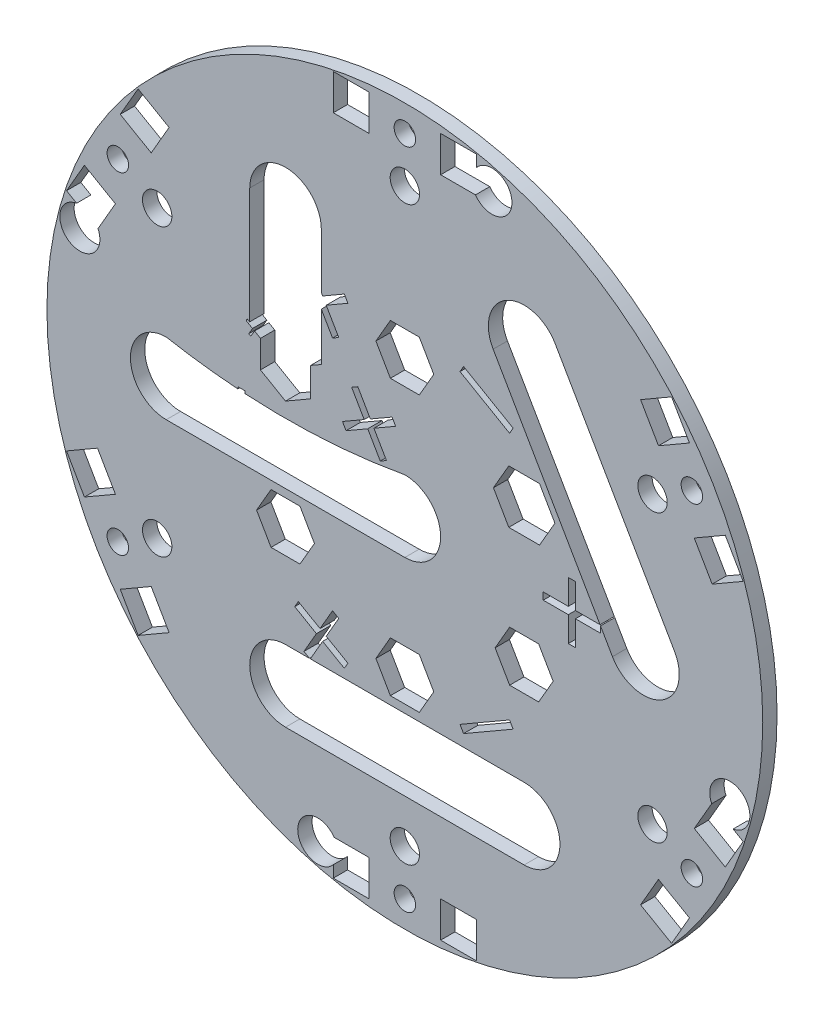
SolidWorks part; units mm, degrees
ref_plane "Plan de face" through (0, 0, 0) normal (0, 0, 1) x (1, 0, 0)
ref_plane "Plan de dessus" through (0, 0, 0) normal (0, 1, 0) x (1, 0, 0)
ref_plane "Plan de droite" through (0, 0, 0) normal (1, 0, 0) x (0, 0, -1)
sketch "Esquisse1" plane through (0, 0, 0) normal (0, 0, 1) x (1, 0, 0)
  line L0 (53.6751, 0) -> (-86.559, 0) construction
  line L1 (0, 50) -> (0, -56.2363) construction
  line L2 (0, 0) -> (70.5826, 40.7509) construction
  line L3 (0, 0) -> (-77.9761, 45.0195) construction
  line L4 (16.6667, 28.8675) -> (33.3333, 0) construction
  line L5 (20.9968, 31.3675) -> (37.6635, 2.5)
  line L6 (12.3365, 26.3675) -> (29.0032, -2.5)
  line L7 (16.6667, -28.8675) -> (-16.6667, -28.8675) construction
  line L8 (16.6667, -33.8675) -> (-16.6667, -33.8675)
  line L9 (16.6667, -23.8675) -> (-16.6667, -23.8675)
  line L10 (-33.3333, 0) -> (0, 0) construction
  line L11 (-21.6707, 12.5116) -> (-20.1709, 11.6468)
  line L12 (-33.3333, -5) -> (0, -5)
  line L13 (-16.6714, 9.6252) -> (-16.6667, 28.8675) construction
  line L14 (-21.6707, 12.5116) -> (-21.6667, 28.8687)
  line L15 (-11.6707, 12.5116) -> (-11.6667, 28.8663)
  line L16 (-13.1709, 11.6451) -> (-11.6707, 12.5116)
  line L17 (-12.6299, -9.6252) -> (-14.6507, -6.1252)
  line L18 (-14.6507, -6.1252) -> (-18.6921, -6.1252)
  line L19 (-18.6921, -6.1252) -> (-20.7128, -9.6252)
  line L20 (-20.7128, -9.6252) -> (-18.6921, -13.1252)
  line L21 (-18.6921, -13.1252) -> (-14.6507, -13.1252)
  line L22 (-14.6507, -13.1252) -> (-12.6299, -9.6252)
  line L23 (2.0207, -15.7328) -> (-2.0207, -15.7328)
  line L24 (-2.0207, -15.7328) -> (-4.0415, -19.2328)
  line L25 (-4.0415, -19.2328) -> (-2.0207, -22.7328)
  line L26 (-2.0207, -22.7328) -> (2.0207, -22.7328)
  line L27 (2.0207, -22.7328) -> (4.0415, -19.2328)
  line L28 (4.0415, -19.2328) -> (2.0207, -15.7328)
  line L29 (14.64, -6.1122) -> (12.6134, -9.6225)
  line L30 (12.6134, -9.6225) -> (14.64, -13.1328)
  line L31 (14.64, -13.1328) -> (18.6933, -13.1328)
  line L32 (18.6933, -13.1328) -> (20.72, -9.6225)
  line L33 (20.72, -9.6225) -> (18.6933, -6.1122)
  line L34 (18.6933, -6.1122) -> (14.64, -6.1122)
  line L35 (20.9633, 9.6242) -> (18.8164, 13.3427)
  line L36 (18.8164, 13.3427) -> (14.5227, 13.3427)
  line L37 (14.5227, 13.3427) -> (12.3758, 9.6242)
  line L38 (12.3758, 9.6242) -> (14.5227, 5.9057)
  line L39 (14.5227, 5.9057) -> (18.8164, 5.9057)
  line L40 (18.8164, 5.9057) -> (20.9633, 9.6242)
  line L41 (4.0415, 19.1653) -> (2.0207, 22.6653)
  line L42 (2.0207, 22.6653) -> (-2.0207, 22.6653)
  line L43 (-2.0207, 22.6653) -> (-4.0415, 19.1653)
  line L44 (-4.0415, 19.1653) -> (-2.0207, 15.6653)
  line L45 (-2.0207, 15.6653) -> (2.0207, 15.6653)
  line L46 (2.0207, 15.6653) -> (4.0415, 19.1653)
  line L47 (-20.1709, 11.6468) -> (-20.1719, 7.6054)
  line L48 (-20.1719, 7.6054) -> (-16.6724, 5.5838)
  line L49 (-16.6724, 5.5838) -> (-13.1719, 7.6036)
  line L50 (-13.1719, 7.6036) -> (-13.1709, 11.6451)
  line L52 (-16.6704, 13.6667) -> (-20.1709, 11.6468) [skipped]
  line L53 (-13.1709, 11.6451) -> (-16.6704, 13.6667) [skipped]
  circle A0 centre (0, 0) radius 50
  circle A1 centre (33.3333, 0) radius 16.6667 construction
  circle A2 centre (16.6667, -28.8675) radius 16.6667 construction
  circle A3 centre (-16.6667, -28.8675) radius 16.6667 construction
  circle A4 centre (-33.3333, 0) radius 16.6667 construction
  circle A5 centre (-16.6667, 28.8675) radius 16.6667 construction
  circle A6 centre (16.6667, 28.8675) radius 16.6667 construction
  circle A7 centre (-34.5978, 19.9751) radius 2.05
  circle A8 centre (0, 39.9502) radius 2.05
  circle A9 centre (34.5978, 19.9751) radius 2.05
  circle A10 centre (34.5978, -19.9751) radius 2.05
  circle A11 centre (0, -39.9502) radius 2.05
  circle A12 centre (-34.5978, -19.9751) radius 2.05
  arc A13 (20.9968, 31.3675) -> (12.3365, 26.3675) centre (16.6667, 28.8675) ccw
  circle A14 centre (0, 0) radius 16.6667 construction
  circle A15 centre (16.6667, -9.6225) radius 3.5103 construction
  circle A17 centre (-16.6714, -9.6252) radius 3.5 construction
  arc A18 (16.6667, -33.8675) -> (16.6667, -23.8675) centre (16.6667, -28.8675) ccw
  arc A20 (-33.3333, 5) -> (-33.3333, -5) centre (-33.3333, 0) ccw
  arc A22 (-16.6667, -23.8675) -> (-16.6667, -33.8675) centre (-16.6667, -28.8675) ccw
  circle A23 centre (0, -19.2328) radius 3.5 construction
  arc A24 (29.0032, -2.5) -> (37.6635, 2.5) centre (33.3333, 0) ccw
  circle A25 centre (16.6696, 9.6242) radius 3.7185 construction
  circle A26 centre (0, 19.1653) radius 3.5 construction
  arc A27 (0, -5) -> (0, 5) centre (0, 0) ccw
  arc A28 (-33.3333, 5) -> (0, 5) centre (-16.6667, 95.7057) ccw
  circle A29 centre (-16.6714, 9.6252) radius 3.5 construction
  arc A35 (-11.6667, 28.8663) -> (-21.6667, 28.8687) centre (-16.6667, 28.8675) ccw
  point P20 (0, 0)
  point P30 (0, 0)
  point P36 (25, 14.4338)
  point P40 (0, -28.8675)
  point P44 (-16.669, 19.2464)
  point P48 (-16.6667, 0)
  point P54 (0, 0)
  point P60 (0, 0)
  point P117 (0, 0)
  line B0 (37.597, -27.4801) -> (42.597, -18.8199) construction
  line B1 (35.4319, -26.2301) -> (32.9319, -30.5603)
  line B2 (35.4319, -26.2301) -> (39.762, -28.7301)
  line B3 (39.762, -28.7301) -> (37.262, -33.0603)
  line B4 (32.9319, -30.5603) -> (37.262, -33.0603)
  line B5 (40.4319, -17.5699) -> (42.9319, -13.2397)
  line B6 (40.4319, -17.5699) -> (44.762, -20.0699)
  line B7 (44.762, -20.0699) -> (47.262, -15.7397)
  line B8 (42.9319, -13.2397) -> (47.262, -15.7397)
  circle B9 centre (40.097, -23.15) radius 1.5
  line B10 (-5, -46.3) -> (5, -46.3) construction
  line B11 (-5, -43.8) -> (-10, -43.8)
  line B12 (-5, -43.8) -> (-5, -48.8)
  line B13 (-5, -48.8) -> (-10, -48.8)
  line B14 (-10, -43.8) -> (-10, -48.8)
  line B15 (5, -43.8) -> (10, -43.8)
  line B16 (5, -43.8) -> (5, -48.8)
  line B17 (5, -48.8) -> (10, -48.8)
  line B18 (10, -43.8) -> (10, -48.8)
  circle B19 centre (0, -46.3) radius 1.5
  line B20 (-42.597, -18.8199) -> (-37.597, -27.4801) construction
  line B21 (-40.4319, -17.5699) -> (-42.9319, -13.2397)
  line B22 (-40.4319, -17.5699) -> (-44.762, -20.0699)
  line B23 (-44.762, -20.0699) -> (-47.262, -15.7397)
  line B24 (-42.9319, -13.2397) -> (-47.262, -15.7397)
  line B25 (-35.4319, -26.2301) -> (-32.9319, -30.5603)
  line B26 (-35.4319, -26.2301) -> (-39.762, -28.7301)
  line B27 (-39.762, -28.7301) -> (-37.262, -33.0603)
  line B28 (-32.9319, -30.5603) -> (-37.262, -33.0603)
  circle B29 centre (-40.097, -23.15) radius 1.5
  line B30 (-37.597, 27.4801) -> (-42.597, 18.8199) construction
  line B31 (-35.4319, 26.2301) -> (-32.9319, 30.5603)
  line B32 (-35.4319, 26.2301) -> (-39.762, 28.7301)
  line B33 (-39.762, 28.7301) -> (-37.262, 33.0603)
  line B34 (-32.9319, 30.5603) -> (-37.262, 33.0603)
  line B35 (-40.4319, 17.5699) -> (-42.9319, 13.2397)
  line B36 (-40.4319, 17.5699) -> (-44.762, 20.0699)
  line B37 (-44.762, 20.0699) -> (-47.262, 15.7397)
  line B38 (-42.9319, 13.2397) -> (-47.262, 15.7397)
  circle B39 centre (-40.097, 23.15) radius 1.5
  line B40 (5, 46.3) -> (-5, 46.3) construction
  line B41 (5, 43.8) -> (10, 43.8)
  line B42 (5, 43.8) -> (5, 48.8)
  line B43 (5, 48.8) -> (10, 48.8)
  line B44 (10, 43.8) -> (10, 48.8)
  line B45 (-5, 43.8) -> (-10, 43.8)
  line B46 (-5, 43.8) -> (-5, 48.8)
  line B47 (-5, 48.8) -> (-10, 48.8)
  line B48 (-10, 43.8) -> (-10, 48.8)
  circle B49 centre (0, 46.3) radius 1.5
  line B50 (42.597, 18.8199) -> (37.597, 27.4801) construction
  line B51 (40.4319, 17.5699) -> (42.9319, 13.2397)
  line B52 (40.4319, 17.5699) -> (44.762, 20.0699)
  line B53 (44.762, 20.0699) -> (47.262, 15.7397)
  line B54 (42.9319, 13.2397) -> (47.262, 15.7397)
  line B55 (35.4319, 26.2301) -> (32.9319, 30.5603)
  line B56 (35.4319, 26.2301) -> (39.762, 28.7301)
  line B57 (39.762, 28.7301) -> (37.262, 33.0603)
  line B58 (32.9319, 30.5603) -> (37.262, 33.0603)
  circle B59 centre (40.097, 23.15) radius 1.5
  dimension "D1" = 6
  dimension "D2" = 30
  dimension "D4" = 6
  dimension "D5" = 10
  dimension "D6" = 46.3
  dimension "D3" = 30
  dimension "D7" = 6
sketch_block_instance "Trou M3 plots 5mm-1"
sketch_block "Trou M3 plots 5mm" parameters "D2"=3, "D1"=5, "D3"=5, "D4"=10
sketch_block_instance "Trou M3 plots 5mm-3"
sketch_block_instance "Trou M3 plots 5mm-4"
sketch_block_instance "Trou M3 plots 5mm-5"
sketch_block_instance "Trou M3 plots 5mm-6"
sketch_block_instance "Trou M3 plots 5mm-7"
extrude "Boss.-Extru.1" add sketch "Esquisse1" along normal blind 2
sketch "Sketch2" plane through (0, 0, 2) normal (0, 0, 1) x (1, 0, 0)
  line L0 (53.6751, 0) -> (-86.559, 0) construction
  line L1 (-173205.0808, -100000) -> (173275.6634, 100040.7509) construction
  arc A0 (-50, 0) -> (-25, -14.4338) centre (-33.3333, 0) ccw
  circle A1 centre (0, 0) radius 50 construction
  arc A2 (-25, -14.4338) -> (-25, -43.3013) centre (-16.6667, -28.8675) ccw
  arc A3 (-25, -43.3013) -> (-50, 0) centre (0, 0) ccw
extrude "Cut-Extrude1" [suppressed] cut sketch "Sketch2" against normal through all contours A2 A3 A0
sketch "Sketch3" plane through (0, 0, 2) normal (0, 0, 1) x (1, 0, 0)
  line L0 (53.6751, 0) -> (-86.559, 0) construction
  line L6 (16.6667, 28.8675) -> (-16.6667, -28.8675) construction
  line L7 (-23.3333, 4) -> (-22.3333, 4)
  line L8 (-23.3333, 4) -> (-23.3333, -4)
  line L9 (-23.3333, -4) -> (-22.3333, -4)
  line L10 (-22.3333, 4) -> (-22.3333, -4)
  line L11 (-16.6667, 28.8675) -> (16.6667, -28.8675) construction
  line L12 (-13.2337, 23.9214) -> (-14.0997, 23.4214)
  line L13 (-14.0997, 23.4214) -> (-12.3497, 20.3903)
  line L14 (-12.3497, 20.3903) -> (-15.3808, 18.6403)
  line L15 (-15.3808, 18.6403) -> (-14.8808, 17.7742)
  line L16 (-14.8808, 17.7742) -> (-11.8497, 19.5242)
  line L17 (-11.8497, 19.5242) -> (-10.0997, 16.4932)
  line L18 (-10.0997, 16.4932) -> (-9.2337, 16.9932)
  line L19 (-9.2337, 16.9932) -> (-10.9837, 20.0242)
  line L20 (-10.9837, 20.0242) -> (-7.9526, 21.7742)
  line L21 (-7.9526, 21.7742) -> (-8.4526, 22.6403)
  line L22 (-8.4526, 22.6403) -> (-11.4837, 20.8903)
  line L23 (-11.4837, 20.8903) -> (-13.2337, 23.9214)
  line L24 (-16.2531, 17.5593) -> (-5.3419, 23.8588) construction
  line L25 (-14.6252, 25.3316) -> (-8.4936, 14.7114) construction
  line L26 (15.1308, 18.2073) -> (14.6308, 17.3412)
  line L27 (15.1308, 18.2073) -> (8.2026, 22.2073)
  line L28 (8.2026, 22.2073) -> (7.7026, 21.3412)
  line L29 (14.6308, 17.3412) -> (7.7026, 21.3412)
  line L30 (8.2026, -22.2073) -> (7.7026, -21.3412)
  line L31 (8.2026, -22.2073) -> (15.1308, -18.2073)
  line L32 (15.1308, -18.2073) -> (14.6308, -17.3412)
  line L33 (7.7026, -21.3412) -> (14.6308, -17.3412)
  line L34 (27.3333, -0.5) -> (27.3333, 0.5)
  line L35 (27.3333, 0.5) -> (23.8333, 0.5)
  line L36 (23.8333, 0.5) -> (23.8333, 4)
  line L37 (23.8333, 4) -> (22.8333, 4)
  line L38 (22.8333, 4) -> (22.8333, 0.5)
  line L39 (22.8333, 0.5) -> (19.3333, 0.5)
  line L40 (19.3333, 0.5) -> (19.3333, -0.5)
  line L41 (19.3333, -0.5) -> (22.8333, -0.5)
  line L42 (22.8333, -0.5) -> (22.8333, -4)
  line L43 (22.8333, -4) -> (23.8333, -4)
  line L44 (23.8333, -4) -> (23.8333, -0.5)
  line L45 (23.8333, -0.5) -> (27.3333, -0.5)
  line L46 (-14.0997, -23.4214) -> (-13.2337, -23.9214)
  line L47 (-13.2337, -23.9214) -> (-11.4837, -20.8903)
  line L48 (-11.4837, -20.8903) -> (-8.4526, -22.6403)
  line L49 (-8.4526, -22.6403) -> (-7.9526, -21.7742)
  line L50 (-7.9526, -21.7742) -> (-10.9837, -20.0242)
  line L51 (-10.9837, -20.0242) -> (-9.2337, -16.9932)
  line L52 (-9.2337, -16.9932) -> (-10.0997, -16.4932)
  line L53 (-10.0997, -16.4932) -> (-11.8497, -19.5242)
  line L54 (-11.8497, -19.5242) -> (-14.8808, -17.7742)
  line L55 (-14.8808, -17.7742) -> (-15.3808, -18.6403)
  line L56 (-15.3808, -18.6403) -> (-12.3497, -20.3903)
  line L57 (-12.3497, -20.3903) -> (-14.0997, -23.4214)
  line L58 (-21.8333, 14.2784) -> (-24.4284, 9.7836) construction
  line L59 (173205.0808, -100000) -> (-173283.0568, 100045.0195) construction
  line L60 (-7.433, 11.8744) -> (-5.683, 8.8433)
  line L61 (-6.567, 12.3744) -> (-7.433, 11.8744)
  line L62 (-7.8805, 13.6494) -> (-1.7489, 3.0291) construction
  line L63 (-2.567, 5.4462) -> (-4.317, 8.4772)
  line L64 (-1.2859, 10.2272) -> (-1.7859, 11.0933)
  line L65 (-3.433, 4.9462) -> (-2.567, 5.4462)
  line L66 (-4.317, 8.4772) -> (-1.2859, 10.2272)
  line L67 (-8.7141, 7.0933) -> (-8.2141, 6.2272)
  line L68 (-8.2141, 6.2272) -> (-5.183, 7.9772)
  line L69 (-4.817, 9.3433) -> (-6.567, 12.3744)
  line L70 (-1.7859, 11.0933) -> (-4.817, 9.3433)
  line L71 (-5.183, 7.9772) -> (-3.433, 4.9462)
  line L72 (-5.683, 8.8433) -> (-8.7141, 7.0933)
  line L73 (-9.0607, 6.3158) -> (-0.8395, 11.0623) construction
  line L74 (-173205.0808, -100000) -> (173275.6634, 100040.7509) construction
  text T0 "+"
  point P2 (-8.4641, 6.6603)
  point P4 (-1.5359, 10.6603)
  point P36 (-8.2026, 22.2073)
  point P39 (-13.6667, 23.6714)
  point P51 (0, 0)
  point P75 (0, 0)
  point P85 (-23.3333, 0)
  point P92 (-1.5413, 10.6572)
  dimension "D2" = 1
  dimension "D3" = 10
  dimension "D4" = 1
  dimension "D5" = 8
  dimension "D6" = 10
  dimension "D7" = 1
  dimension "D8" = 1
  dimension "D9" = 8
  dimension "D10" = 8
  dimension "D11" = 4
  dimension "D12" = 4
  dimension "D13" = 10
  dimension "D16" = 1
  dimension "D14" = 3
  dimension "D15" = 3
extrude "Cut-Extrude2" cut sketch "Sketch3" against normal blind 10
sketch "Sketch4" plane through (0, 0, 2) normal (0, 0, 1) x (1, 0, 0)
  line L0 (-0.2034, -0.7591) -> (-16.9538, -63.2725) construction
  line L1 (0, 0) -> (0, -46.3) construction
  circle A0 centre (-12.1645, -45.3985) radius 2.8
  circle A1 centre (-45.3985, 12.1645) radius 2.8
  circle A2 centre (12.1645, 45.3985) radius 2.8
  circle A3 centre (45.3985, -12.1645) radius 2.8
  point P18 (0, 0)
  dimension "D2" = 47
  dimension "D1" = 15
  dimension "D3" = 4
extrude "Cut-Extrude4" cut sketch "Sketch4" against normal blind 10
